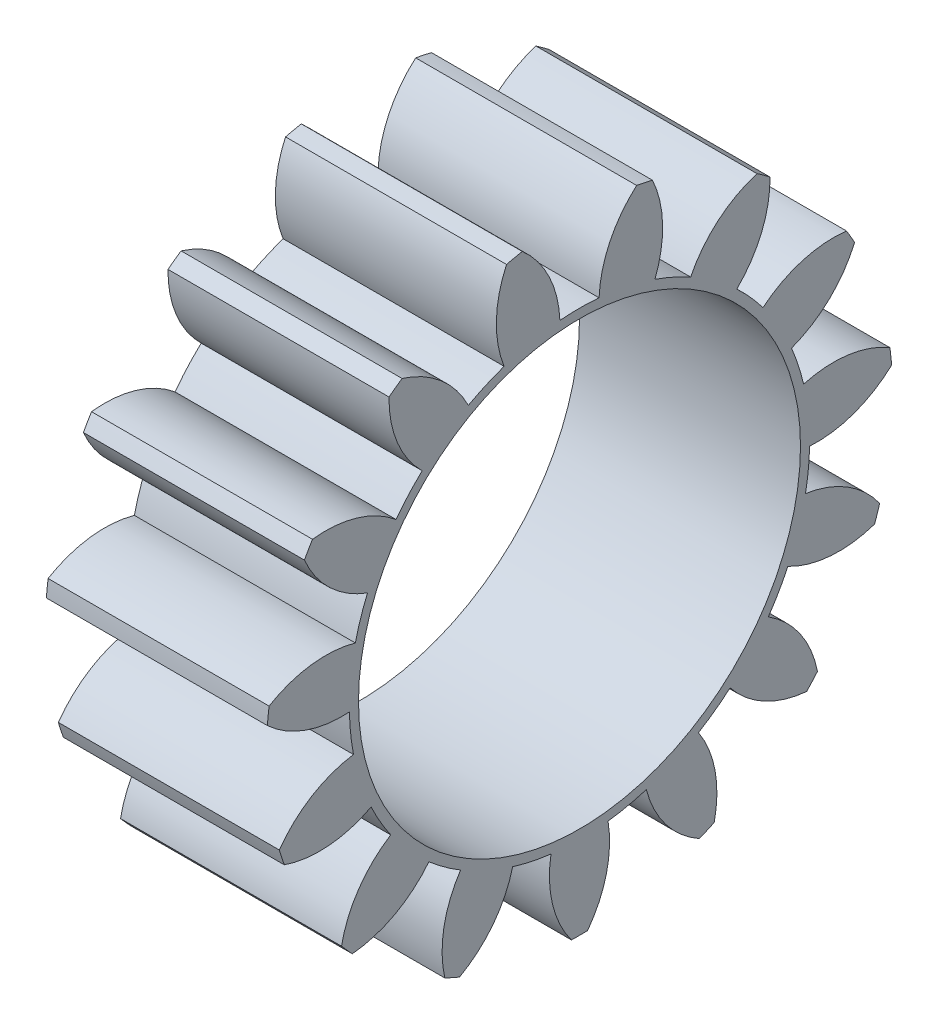
SolidWorks part; units mm, degrees
ref_plane "Plane1" through (0, 0, 0) normal (0, 0, 1) x (1, 0, 0)
ref_plane "Plane2" through (0, 0, 0) normal (0, 1, 0) x (1, 0, 0)
ref_plane "Plane3" through (0, 0, 0) normal (1, 0, 0) x (0, 0, -1)
sketch "HoldingSke" plane through (0, 0, 0) normal (0, 1, 0) x (1, 0, 0)
  line L0 (0, 0) -> (1.9319, -0.5176)
  line L1 (-15, 0) -> (100, 0) construction
  line L2 (0, 0) -> (-2.1039, 2.3779)
  line L3 (0, 0) -> (-11.863, 4.5341)
  line L4 (0, 0) -> (8.3417, 2.2352)
  line L5 (0, 0) -> (-46.8476, -17.4728)
  line L6 (0, 0) -> (-2.4869, -1.6779)
  line L7 (-2.1039, 2.3779) -> (8.6586, 51.2059)
  line L8 (-76.2, 54.61) -> (-75.2, 54.61)
  line L9 (-71.009, 38.7566) -> (-53.1078, 45.2721)
  line L10 (-76.2, 71.12) -> (104.1128, 71.12)
  line L11 (0, 0) -> (-3, 0)
  line L12 (-76.2, 101.6) -> (-76.181, 101.6)
  line L13 (24.9733, 27.94) -> (52.9518, 28.4284)
  line L14 (24.9733, 27.94) -> (24.9743, 27.94)
  line L15 (24.9733, 27.94) -> (100.4006, 29.5858)
  line L16 (-63.627, -0.5) -> (-12.827, -0.5)
  circle A0 centre (0, 0) radius 3
  circle A1 centre (0, 0) radius 3.124
  circle A2 centre (0, 0) radius 37.5
  circle A3 centre (0, 0) radius 3
  dimension "MHD" = 6.248
  dimension "Hub_dia" = 75
  dimension "Bore" = 6
  dimension "MBD" = 6
  dimension "Num_teeth" = 15
  dimension "Pitch" = 2
  dimension "Overall_len" = 50
  dimension "Show_teeth" = 15
  dimension "Thickness" = 3
  dimension "OAL" = 50.0001
  dimension "T_dim" = 1
  dimension "Ap" = 20
  dimension "H" = 19.05
  dimension "Pitch_radius" = 180.3128
  dimension "Width" = 3
  dimension "Backlash" = 0.019
  dimension "Addendum_fac" = 1
  dimension "Dedendum_fac" = 1.25
  dimension "Clearance_fac" = 0.25
  dimension "Dedendum_add" = 0.001
  dimension "Module" = 0.5
sketch "BasProSke" plane through (0, 0, 0) normal (0, 1, 0) x (1, 0, 0)
  line L0 (-10, 0) -> (60, 0) construction
  line L1 (0, 0) -> (0, 4.25)
  line L2 (0, 0) -> (3, 0)
  line L3 (3, 0) -> (3, 4.25)
  line L4 (3, 4.25) -> (0, 4.25)
  dimension "Thickness" = 3
  dimension "Diameter" = 8.5
revolve "Base-Revolve" add sketch "BasProSke" angle 360 about L0
sketch "TooCutSke" plane through (0, 0, 0) normal (1, 0, 0) x (0, 0, -1)
  line L1 (0, 0) -> (0, 107) construction
  line L2 (0, 0) -> (-0.4252, 3.7258) construction
  line L3 (0, 0) -> (-1.5522, 7.3025) construction
  line L4 (-0.4252, 3.7258) -> (-0.7761, 3.6512) construction
  arc A0 (0.2658, 3.1127) -> (-0.2658, 3.1127) centre (0, 0) ccw
  arc A1 (0.8008, 4.1997) -> (-0.8008, 4.1997) centre (0, 0) ccw
  circle A2 centre (0, 0) radius 3.75 construction
  circle A3 centre (0, 0) radius 3.5238 construction
  arc A4 (-0.2658, 3.1127) -> (-0.8008, 4.1997) centre (-1.7645, 3.0503) ccw
  arc A5 (0.8008, 4.1997) -> (0.2658, 3.1127) centre (1.7645, 3.0503) ccw
  dimension "Root_dia" = 6.248
  dimension "Overcut_dia" = 8.5508
  dimension "Pitch_dia" = 7.5
  dimension "Base_dia" = 7.0477
  dimension "Flank_rad" = 1.5
  dimension "Half_ang" = 12
  dimension "Half_CT" = 0.3587
extrude "ToothCut" cut sketch "TooCutSke" along normal through all
fillet "Breaks" [suppressed] radius 0.01
fillet "RootFillets" [suppressed] radius 0.126
pattern_circular "TeethCuts" count 15 every 24 about axis through (-10, 0, 0) along (1, 0, 0) of "ToothCut", "RootFillets", "Breaks"
sketch "HubNeaOneSke" plane through (0, 0, 0) normal (-1, 0, 0) x (0, 0, 1)
  circle A0 centre (0, 0) radius 3.124
  dimension "Diameter" = 6.248
extrude "HubNearOne" [suppressed] add sketch "HubNeaOneSke" along normal blind 47.0001
sketch "HubNeaBotSke" plane through (0, 0, 0) normal (-1, 0, 0) x (0, 0, 1)
  circle A0 centre (0, 0) radius 3.124
  dimension "Diameter" = 6.248
extrude "HubNearBoth" [suppressed] add sketch "HubNeaBotSke" along normal blind 23.5
ref_plane "FarPln" through (3, 0, 0) normal (1, 0, 0) x (0, 0, -1)
sketch "HubFarSke" plane through (3, 0, 0) normal (1, 0, 0) x (0, 0, -1)
  circle A0 centre (0, 0) radius 3.124
  dimension "Diameter" = 6.248
extrude "HubFar" [suppressed] add sketch "HubFarSke" along normal blind 23.5
sketch "BorSke" plane through (0, 0, 0) normal (1, 0, 0) x (0, 0, -1)
  circle A0 centre (0, 0) radius 3
  dimension "Diameter" = 6
extrude "Bore" cut sketch "BorSke" along normal mid plane 100.0001
sketch "KeySke" plane through (0, 0, 0) normal (1, 0, 0) x (0, 0, -1)
  line L0 (-1, 0) -> (-1, 4)
  line L1 (-1, 4) -> (1, 4)
  line L2 (1, 4) -> (1, 0)
  line L3 (0, 0) -> (0, 34) construction
  line L4 (-1, 0) -> (1, 0)
  dimension "Offset" = 4
  dimension "Width" = 2
extrude "Keyway" [suppressed] cut sketch "KeySke" along normal mid plane 100.0001
pattern_circular "Keyway2" [suppressed] count 2 every 90 about axis through (-10, 0, 0) along (1, 0, 0)
equation "' \"Module@HoldingSke\" = 6.35"
equation "' \"Num_teeth@HoldingSke\" = 12"
equation "' \"Ap@HoldingSke\" =  20"
equation "' \"Ap@HoldingSke\" = 20"
equation "' \"Width@HoldingSke\" = 0.5 * 25.4"
equation "' \"Hub_dia@HoldingSke\"= 1 * 25.4"
equation "' \"Hub_dia@HoldingSke\" = 1 * 25.4"
equation "' \"Overall_len@HoldingSke\" = 1.0 * 25.4"
equation "' \"Bore@HoldingSke\" = 0.75 * 25.4"
equation "' \"T_dim@HoldingSke\" = 0.1 * 25.4"
equation "' \"Width@KeySke\" = 0.25 * 25.4"
equation "' \"Show_teeth@HoldingSke\" = 13"
equation "' \"Backlash@HoldingSke\" = 0.009 * 25.4"
equation "' \"Addendum_fac@HoldingSke\" = 1.0"
equation "' \"Dedendum_fac@HoldingSke\" = 1.25"
equation "' \"Dedendum_add@HoldingSke\" = 0.00005 * 25.4"
equation "' \"Clearance_fac@HoldingSke\" = 0.25"
equation "\"Pitch@HoldingSke\" = 1 / \"Module@HoldingSke\""
equation "\"Overcut_dia@TooCutSke\" = (\"Num_teeth@HoldingSke\" + 2 * \"Addendum_fac@HoldingSke\") / \"Pitch@HoldingSke\" + 0.002 * 25.4"
equation "\"Pitch_dia@TooCutSke\" = \"Num_teeth@HoldingSke\" / \"Pitch@HoldingSke\""
equation "\"Base_dia@TooCutSke\" = \"Num_teeth@HoldingSke\" / \"Pitch@HoldingSke\" * cos((\"Ap@HoldingSke\"  * 3.14159265 / 180))"
equation "\"Root_dia@TooCutSke\" = (\"Num_teeth@HoldingSke\" + 2) / \"Pitch@HoldingSke\" - 2 * (\"Addendum_fac@HoldingSke\" + \"Dedendum_fac@HoldingSke\") / \"Pitch@HoldingSke\" - \"Dedendum_add@HoldingSke\" * 2"
equation "\"Half_ang@TooCutSke\" = 180 / \"Num_teeth@HoldingSke\""
equation "\"Half_CT@TooCutSke\" = \"Num_teeth@HoldingSke\" / \"Pitch@HoldingSke\" * sin((3.14159265 / 2 / \"Num_teeth@HoldingSke\")) / 2 - 7 * \"Backlash@HoldingSke\" / 4"
equation "\"Flank_rad@TooCutSke\" = \"Num_teeth@HoldingSke\" / \"Pitch@HoldingSke\" / 5"
equation "\"Radius@RootFillets\" = \"Clearance_fac@HoldingSke\" / \"Pitch@HoldingSke\" + \"Dedendum_add@HoldingSke\""
equation "\"Break_rad@Breaks\" = 0.02 / \"Pitch@HoldingSke\""
equation "\"Thickness@HoldingSke\" = \"Width@HoldingSke\""
equation "\"OAL@HoldingSke\" = \"Thickness@HoldingSke\""
equation "\"MHD@HoldingSke\" = (\"Num_teeth@HoldingSke\" + 2) / \"Pitch@HoldingSke\" - 2 * (\"Addendum_fac@HoldingSke\" + \"Dedendum_fac@HoldingSke\")  / \"Pitch@HoldingSke\" - \"Dedendum_add@HoldingSke\" * 2"
equation "\"MBD@HoldingSke\" = (\"Num_teeth@HoldingSke\" + 2) / \"Pitch@HoldingSke\" - 2 * (\"Addendum_fac@HoldingSke\" + \"Dedendum_fac@HoldingSke\")  / \"Pitch@HoldingSke\" - \"Dedendum_add@HoldingSke\" * 2 - 0.002 * 25.4"
equation "\"MHD@HoldingSke\" = ((sgn( \"MHD@HoldingSke\" - \"Hub_dia@HoldingSke\" )-1)*( \"MHD@HoldingSke\" - \"Hub_dia@HoldingSke\" ))/-2+ \"Hub_dia@HoldingSke\""
equation "\"MBD@HoldingSke\" = ((sgn( \"MBD@HoldingSke\" - \"Bore@HoldingSke\" )-1)*( \"MBD@HoldingSke\" - \"Bore@HoldingSke\" ))/-2+ \"Bore@HoldingSke\""
equation "\"OAL@HoldingSke\" = ((sgn( \"OAL@HoldingSke\" - \"Overall_len@HoldingSke\" )+1)*( \"OAL@HoldingSke\" - \"Overall_len@HoldingSke\" ))/2 + \"Overall_len@HoldingSke\" + 0.000002 * 25.4"
equation "\"Num_teeth@TeethCuts\" = int( \"Show_teeth@HoldingSke\" ) + 1"
equation "\"Num_teeth@TeethCuts\" = ((sgn( \"Num_teeth@TeethCuts\" - \"Num_teeth@HoldingSke\" )-1)*( \"Num_teeth@TeethCuts\" - \"Num_teeth@HoldingSke\" ))/-2+ \"Num_teeth@HoldingSke\""
equation "\"Num_teeth@TeethCuts\" = ((sgn( \"Num_teeth@TeethCuts\" - 2.0)+1)*( \"Num_teeth@TeethCuts\" - 2.0))/2 +2.0"
equation "\"Angle@TeethCuts\" = 360.0 / \"Num_teeth@HoldingSke\""
equation "\"Diameter@BasProSke\" = (\"Num_teeth@HoldingSke\" + 2 * \"Addendum_fac@HoldingSke\") / \"Pitch@HoldingSke\""
equation "\"Thickness@BasProSke\"  = \"Thickness@HoldingSke\""
equation "' \"Fillet_rad@BasProSke\" =  \"Thickness@HoldingSke\" * 0.05"
equation "' \"Fillet_rad@BasProSke\" = \"Thickness@HoldingSke\" * 0.05"
equation "\"MHD@HoldingSke\" = ((sgn( \"MHD@HoldingSke\" - \"Root_dia@TooCutSke\" )-1)*( \"MHD@HoldingSke\" - \"Root_dia@TooCutSke\" ))/-2+ \"Root_dia@TooCutSke\""
equation "\"Diameter@HubNeaOneSke\" = \"MHD@HoldingSke\""
equation "\"Length@HubNearOne\" = \"OAL@HoldingSke\" - \"Thickness@BasProSke\""
equation "\"Diameter@HubNeaBotSke\" = \"MHD@HoldingSke\""
equation "\"Length@HubNearBoth\" = ( \"OAL@HoldingSke\" - \"Thickness@BasProSke\" ) / 2.0"
equation "\"Thickness@FarPln\" = \"Thickness@BasProSke\""
equation "\"Diameter@HubFarSke\" = \"MHD@HoldingSke\""
equation "\"Length@HubFar\" = ( \"OAL@HoldingSke\" - \"Thickness@BasProSke\" ) / 2.0"
equation "\"Diameter@BorSke\" = \"MBD@HoldingSke\""
equation "\"D1@Bore\" = \"OAL@HoldingSke\" * 2.0"
equation "\"D1@Keyway\" = \"OAL@HoldingSke\" * 2.0"
equation "\"Offset@KeySke\" = \"T_dim@HoldingSke\" + \"MBD@HoldingSke\" / 2.0"
